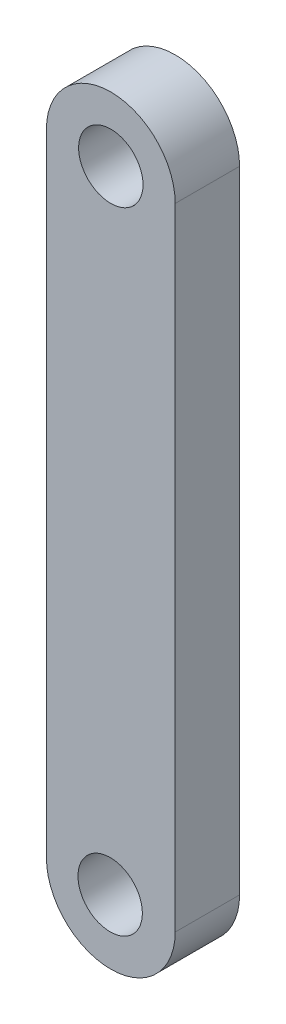
SolidWorks part; units mm, degrees
ref_plane "Front Plane" through (0, 0, 0) normal (0, 0, 1) x (1, 0, 0)
ref_plane "Top Plane" through (0, 0, 0) normal (0, 1, 0) x (1, 0, 0)
ref_plane "Right Plane" through (0, 0, 0) normal (1, 0, 0) x (0, 0, -1)
sketch "Sketch1" plane through (0, 0, 0) normal (0, 0, 1) x (1, 0, 0)
  line L0 (0, 0) -> (0, 19.6) construction
  line L1 (-2, 0) -> (-2, 19.6)
  line L2 (2, 0) -> (2, 19.6)
  arc A0 (-2, 0) -> (2, 0) centre (0, 0) ccw
  arc A1 (2, 19.6) -> (-2, 19.6) centre (0, 19.6) ccw
  circle A2 centre (0, 19.6) radius 1
  circle A6 centre (-0.0195, -0.0038) radius 1
  circle A7 centre (-0.0195, -0.0038) radius 1.25 construction
  point P3 (0, 9.8)
  dimension "D2" = 2
  dimension "D3" = 2
  dimension "D4" = 2
  dimension "D1" = 19.6
extrude "Boss-Extrude1" add sketch "Sketch1" along normal blind 2
